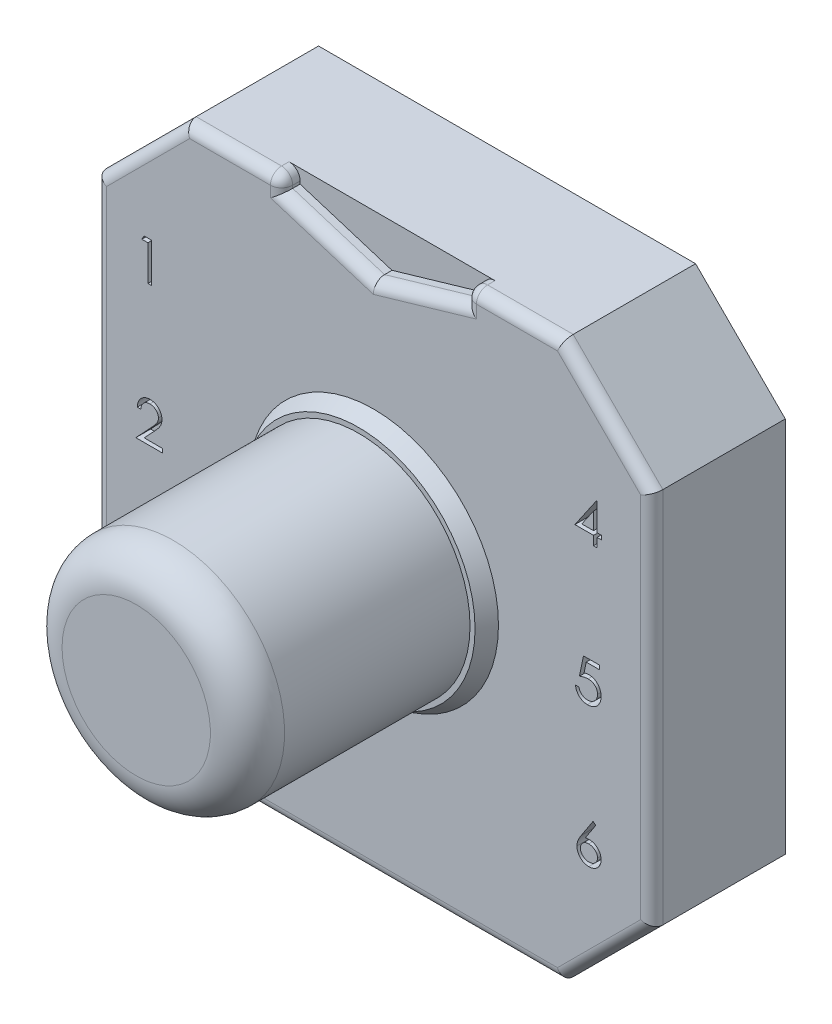
SolidWorks part; units mm, degrees
ref_plane "Plan de face" through (0, 0, 0) normal (0, 0, 1) x (1, 0, 0)
ref_plane "Plan de dessus" through (0, 0, 0) normal (0, 1, 0) x (1, 0, 0)
ref_plane "Plan de droite" through (0, 0, 0) normal (1, 0, 0) x (0, 0, -1)
sketch "Esquisse1" plane through (0, 0, 0) normal (0, 0, 1) x (1, 0, 0)
  line L0 (0, 7.5) -> (7.5, 0) construction
  line L1 (0, 0) -> (7.5, 0)
  line L2 (0, 0) -> (0, 7.5)
  line L3 (0, 7.5) -> (7.5, 7.5)
  line L4 (7.5, 0) -> (7.5, 7.5)
  line L5 (7.5, 7.5) -> (0, 0) construction
  dimension "D1" = 7.5
  dimension "D2" = 7.5
sketch "Esquisse2" plane through (0, 0, 0) normal (0, 0, 1) x (1, 0, 0)
  line L0 (0, 6.2925) -> (1.2075, 7.5)
  line L1 (0, 0) -> (0, 7.5) construction
  line L2 (0, 7.5) -> (7.5, 7.5) construction
  line L3 (1.2075, 7.5) -> (0, 7.5) construction
  line L4 (7.5, 7.5) -> (6.2908, 7.5) construction
  line L5 (6.2908, 7.5) -> (7.5, 6.2925)
  line L6 (7.5, 0) -> (7.5, 7.5) construction
  line L7 (6.2908, 7.5) -> (6.2908, -1.2267) construction
  line L8 (1.2075, 7.5) -> (1.2075, -1.2935) construction
  line L9 (6.2908, 0) -> (7.5, 1.2092)
  line L10 (0, 0) -> (7.5, 0) construction
  line L11 (1.2075, 0) -> (0, 1.2075)
  line L12 (0, 6.2925) -> (0, 1.2075)
  line L13 (1.2075, 0) -> (6.2908, 0)
  line L14 (7.5, 1.2092) -> (7.5, 6.2925)
  line L15 (1.2075, 7.5) -> (6.2908, 7.5)
extrude "Boss.-Extru.1" add sketch "Esquisse2" along normal blind 1.8
sketch "Esquisse3" plane through (0, 0, 0) normal (0, 0, -1) x (-1, 0, 0)
  line L0 (0, 7.5) -> (-7.5, 0) construction
  circle A0 centre (-3.75, 3.75) radius 1.5
extrude "Boss.-Extru.2" add sketch "Esquisse3" against normal blind 5
fillet "Congé2" radius 0.5 1 edges at (2.25, 3.75, 5)
sketch "Esquisse4" plane through (0, 0, 1.8) normal (0, 0, 1) x (1, 0, 0)
  line L0 (1.2075, 7.5) -> (2.5092, 7.5) construction
  line L1 (0, 7.5) -> (7.5, 7.5) construction
  line L2 (6.2908, 7.5) -> (4.9861, 7.5) construction
  line L3 (2.5092, 7.5) -> (4.9861, 7.5)
  line L4 (4.9861, 7.5) -> (4.9861, 7.288)
  line L5 (4.9861, 7.288) -> (3.7477, 6.926)
  line L6 (3.7477, 6.926) -> (2.5092, 7.3132)
  line L7 (2.5092, 7.5) -> (2.5092, 7.3132)
extrude "Enlèv. mat.-Extru.1" cut sketch "Esquisse4" against normal blind 0.25
fillet "Congé5" radius 0.15 4 edges at (4.9861, 7.394, 1.8) (4.3669, 7.107, 1.8) (3.1285, 7.1196, 1.8) (2.5092, 7.4066, 1.8)
fillet "Congé6" radius 0.15 13 edges at (4.9861, 7.5, 1.6) (5.03, 7.5, 1.7561) (2.5092, 7.5, 1.6) (2.4653, 7.5, 1.7561) (0.6038, 0.6038, 1.8) (3.7492, 0, 1.8) (6.8954, 0.6046, 1.8) (7.5, 3.7508, 1.8) (6.8954, 6.8962, 1.8) (5.7135, 7.5, 1.8) (0, 3.75, 1.8) (0.6038, 6.8962, 1.8) (1.7834, 7.5, 1.8)
sketch "Esquisse5" plane through (0, 0, 1.8) normal (0, 0, 1) x (1, 0, 0)
  line L0 (0, 7.5) -> (7.5, 0) construction
  circle A0 centre (3.75, 3.75) radius 1.6833
extrude "Boss.-Extru.3" add sketch "Esquisse5" along normal blind 0.2 draft 30
sketch "Esquisse6" plane through (0, 0, 1.8) normal (0, 0, 1) x (1, 0, 0)
  text T0 "1\r\n2\r\n3" font "Century Gothic" height in points 2
extrude "Enlèv. mat.-Extru.2" cut sketch "Esquisse6" against normal blind 0.2
sketch "Esquisse7" plane through (0, 0, 1.8) normal (0, 0, 1) x (1, 0, 0)
  text T0 "4\r\n5\r\n6" font "Century Gothic" height in points 2
extrude "Enlèv. mat.-Extru.3" cut sketch "Esquisse7" against normal blind 0.2
